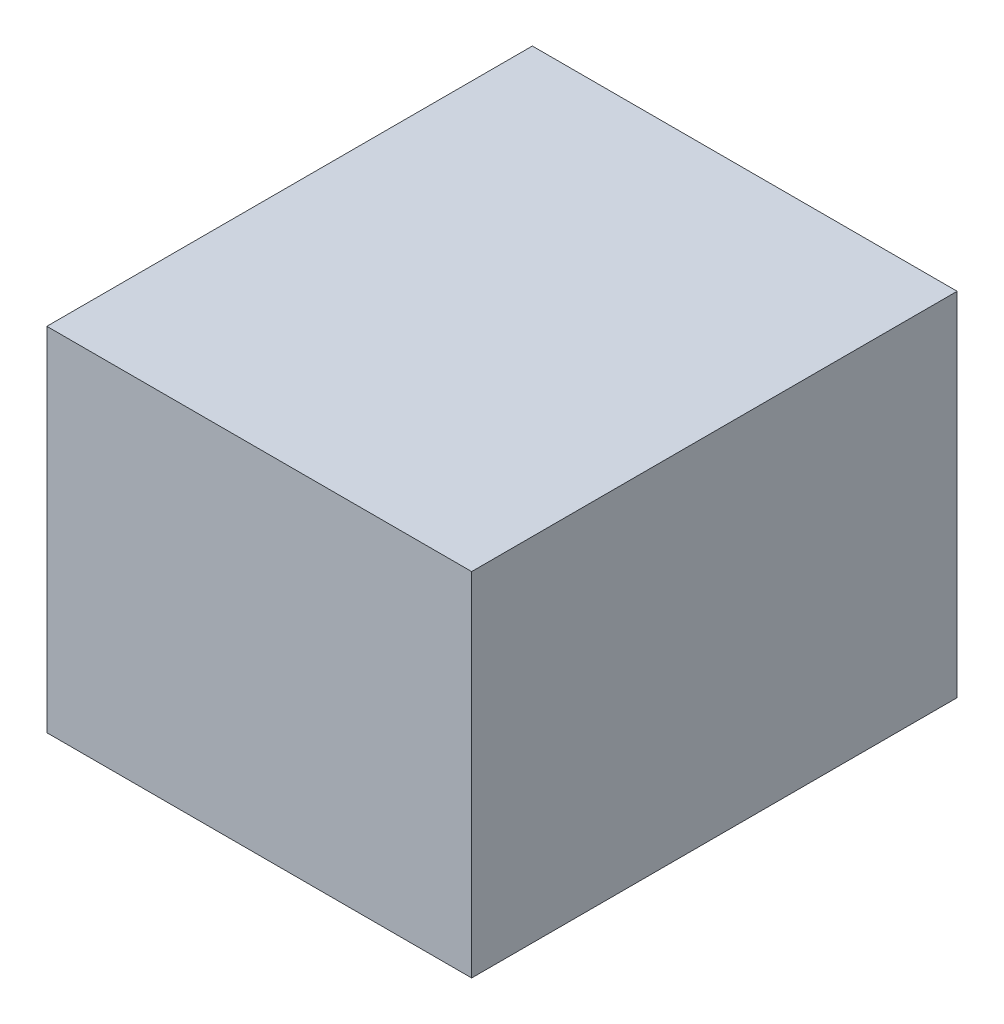
SolidWorks part; units mm, degrees
material "PLA"
ref_plane "Alzado" through (0, 0, 0) normal (0, 0, 1) x (1, 0, 0)
ref_plane "Planta" through (0, 0, 0) normal (0, 1, 0) x (1, 0, 0)
ref_plane "Vista lateral" through (0, 0, 0) normal (1, 0, 0) x (0, 0, -1)
sketch "Croquis1" plane through (0, 0, 0) normal (0, 1, 0) x (1, 0, 0)
  line L1 (17.5, 20) -> (-17.5, 20)
  line L2 (17.5, 20) -> (17.5, -20)
  line L3 (17.5, -20) -> (-17.5, -20)
  line L4 (-17.5, 20) -> (-17.5, -20)
  line L5 (17.5, 20) -> (-17.5, -20) construction
  line L6 (17.5, -20) -> (-17.5, 20) construction
  point P0 (0, 0)
  dimension "D1" = 40
  dimension "D2" = 35
extrude "Saliente-Extruir1" add sketch "Croquis1" along normal blind 29
